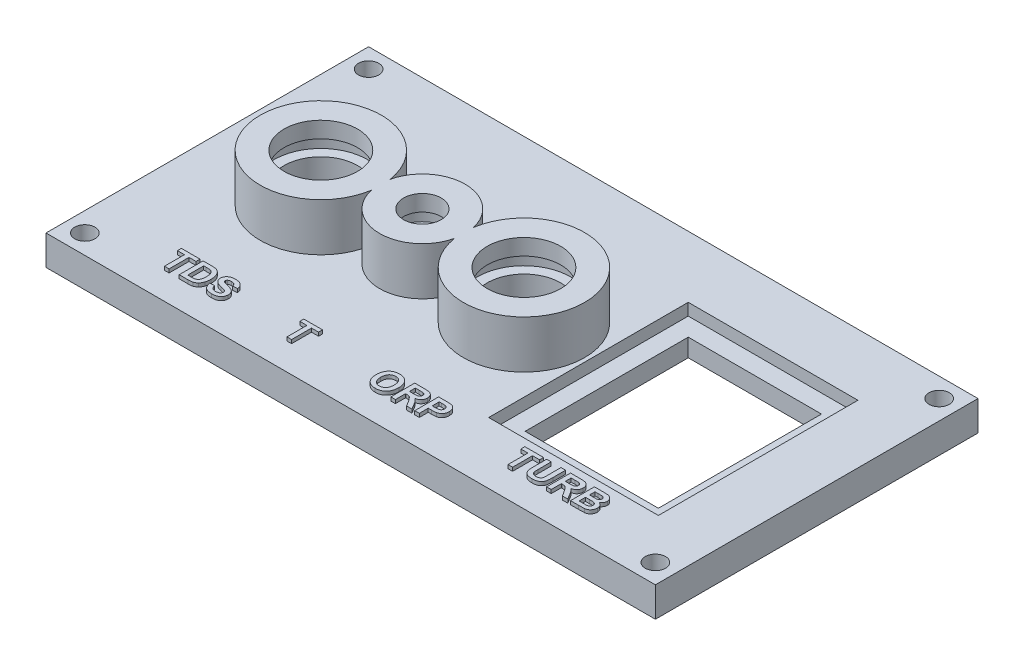
SolidWorks part; units mm, degrees
material "PETG"
ref_plane "Front Plane" through (0, 0, 0) normal (0, 0, 1) x (1, 0, 0)
ref_plane "Top Plane" through (0, 0, 0) normal (0, 1, 0) x (1, 0, 0)
ref_plane "Right Plane" through (0, 0, 0) normal (1, 0, 0) x (0, 0, -1)
other "Configuration Table"
sketch "Sketch1" plane through (0, 0, 0) normal (0, 1, 0) x (1, 0, 0)
  line L0 (-51, -27) -> (51, -27)
  line L1 (51, -27) -> (51, 27)
  line L2 (51, 27) -> (-51, 27)
  line L3 (-51, 27) -> (-51, -27)
extrude "Cap_Plate" add sketch "Sketch1" along normal blind 5
sketch "Sketch2" plane through (0, 0, 0) normal (0, 1, 0) x (1, 0, 0)
  circle A0 centre (-32, 0) radius 10.15
  dimension "D1" = 20.3
extrude "Collar_TDS" add sketch "Sketch2" along normal blind 8 from offset 5
sketch "Sketch3" plane through (0, 0, 0) normal (0, 1, 0) x (1, 0, 0)
  circle A0 centre (-15, 0) radius 7.15
  dimension "D1" = 14.3
extrude "Collar_T" add sketch "Sketch3" along normal blind 8 from offset 5
sketch "Sketch4" plane through (0, 0, 0) normal (0, 1, 0) x (1, 0, 0)
  circle A0 centre (2, 0) radius 10.15
  dimension "D1" = 20.3
extrude "Collar_ORP" add sketch "Sketch4" along normal blind 8 from offset 5
sketch "Sketch5" plane through (0, 0, 0) normal (0, 1, 0) x (1, 0, 0)
  circle A0 centre (-32, 0) radius 6.15
  dimension "D1" = 12.3
extrude "Port_TDS" cut sketch "Sketch5" along normal through all and the other way through all
sketch "Sketch6" plane through (0, 0, 0) normal (0, 1, 0) x (1, 0, 0)
  circle A0 centre (-32, 0) radius 7.85
  dimension "D1" = 15.7
extrude "ORing_Groove_TDS" cut sketch "Sketch6" along normal blind 2.6 from offset 7.7
sketch "Sketch7" plane through (0, 0, 0) normal (0, 1, 0) x (1, 0, 0)
  circle A0 centre (-15, 0) radius 3.15
  dimension "D1" = 6.3
extrude "Port_T" cut sketch "Sketch7" along normal through all and the other way through all
sketch "Sketch8" plane through (0, 0, 0) normal (0, 1, 0) x (1, 0, 0)
  circle A0 centre (-15, 0) radius 4.85
  dimension "D1" = 9.7
extrude "ORing_Groove_T" cut sketch "Sketch8" along normal blind 2.6 from offset 7.7
sketch "Sketch9" plane through (0, 0, 0) normal (0, 1, 0) x (1, 0, 0)
  circle A0 centre (2, 0) radius 6.15
  dimension "D1" = 12.3
extrude "Port_ORP" cut sketch "Sketch9" along normal through all and the other way through all
sketch "Sketch10" plane through (0, 0, 0) normal (0, 1, 0) x (1, 0, 0)
  circle A0 centre (2, 0) radius 7.85
  dimension "D1" = 15.7
extrude "ORing_Groove_ORP" cut sketch "Sketch10" along normal blind 2.6 from offset 7.7
sketch "Sketch11" plane through (0, 0, 0) normal (0, 1, 0) x (1, 0, 0)
  line L1 (15.85, -13.65) -> (38.15, -13.65)
  line L2 (15.85, -13.65) -> (15.85, 13.65)
  line L3 (15.85, 13.65) -> (38.15, 13.65)
  line L4 (38.15, -13.65) -> (38.15, 13.65)
  line L5 (15.85, -13.65) -> (38.15, 13.65) construction
  line L6 (15.85, 13.65) -> (38.15, -13.65) construction
  point P5 (27, 0)
  dimension "D1" = 22.3
  dimension "D2" = 27.3
extrude "Port_TURB" cut sketch "Sketch11" along normal through all and the other way through all
sketch "Sketch12" plane through (0, 0, 0) normal (0, 1, 0) x (1, 0, 0)
  line L1 (12.8, -16.7) -> (41.2, -16.7)
  line L2 (12.8, -16.7) -> (12.8, 16.7)
  line L3 (12.8, 16.7) -> (41.2, 16.7)
  line L4 (41.2, -16.7) -> (41.2, 16.7)
  line L5 (12.8, -16.7) -> (41.2, 16.7) construction
  line L6 (12.8, 16.7) -> (41.2, -16.7) construction
  point P5 (27, 0)
  dimension "D1" = 28.4
  dimension "D2" = 33.4
extrude "TURB_Gasket_Seat" cut sketch "Sketch12" against normal blind 2 from offset 5
sketch "Sketch13" plane through (0, 0, 0) normal (0, 1, 0) x (1, 0, 0)
  circle A0 centre (-47.75, 23.75) radius 1.7
  circle A1 centre (-47.75, -23.75) radius 1.7
  circle A2 centre (47.75, 23.75) radius 1.7
  circle A3 centre (47.75, -23.75) radius 1.7
  dimension "D1" = 3.4
  dimension "D2" = 3.4
  dimension "D3" = 3.4
  dimension "D4" = 3.4
extrude "Screw_Holes_M3" cut sketch "Sketch13" along normal through all and the other way through all
sketch "Sketch14" plane through (0, 0, 0) normal (0, 1, 0) x (1, 0, 0)
  text T0 "TDS" font "Arial" height 4
extrude "Label_TDS" add sketch "Sketch14" along normal blind 0.6 from offset 5
sketch "Sketch15" plane through (0, 0, 0) normal (0, 1, 0) x (1, 0, 0)
  text T0 "T" font "Arial" height 4
extrude "Label_T" add sketch "Sketch15" along normal blind 0.6 from offset 5
sketch "Sketch16" plane through (0, 0, 0) normal (0, 1, 0) x (1, 0, 0)
  text T0 "ORP" font "Arial" height 4
extrude "Label_ORP" add sketch "Sketch16" along normal blind 0.6 from offset 5
sketch "Sketch17" plane through (0, 0, 0) normal (0, 1, 0) x (1, 0, 0)
  text T0 "TURB" font "Arial" height 4
extrude "Label_TURB" add sketch "Sketch17" along normal blind 0.6 from offset 5
equation "\"Jar_OD\"= 90  'ASSUMED - Part C fallback - jar outer diameter"
equation "\"Jar_H\"= 120  'ASSUMED - Part C fallback - jar height"
equation "\"Pump_L\"= 45  'ASSUMED - Part C fallback"
equation "\"Pump_W\"= 24  'ASSUMED - Part C fallback"
equation "\"Pump_H\"= 33  'ASSUMED - Part C fallback"
equation "\"Pump_Outlet_OD\"= 7.5  'ASSUMED - Part C fallback"
equation "\"Tube_OD\"= 8  'ASSUMED - Part C fallback"
equation "\"Tube_ID\"= 6  'ASSUMED - Part C fallback"
equation "\"TDS_Body_Dia\"= 12  'ASSUMED - Part C fallback"
equation "\"TDS_Wet_Len\"= 45  'ASSUMED - Part C fallback - length in water"
equation "\"DS_Tube_Dia\"= 6  'ASSUMED - Part C fallback"
equation "\"DS_Tube_Len\"= 50  'ASSUMED - Part C fallback"
equation "\"ORP_Body_Dia\"= 12  'ASSUMED - Part C fallback"
equation "\"ORP_Body_Len\"= 150  'ASSUMED - Part C fallback"
equation "\"ORP_Cap_Dia\"= 16  'ASSUMED - Part C fallback"
equation "\"Turb_W\"= 33  'ASSUMED - Part C fallback - head width"
equation "\"Turb_D\"= 28  'ASSUMED - Part C fallback - head depth"
equation "\"Turb_H\"= 30  'ASSUMED - Part C fallback - head height"
equation "\"Turb_Slot_W\"= 10  'ASSUMED - Part C fallback - slot width"
equation "\"Flow_L\"= 62  'ASSUMED - Part C fallback YF-S201"
equation "\"Flow_W\"= 36  'ASSUMED - Part C fallback"
equation "\"Flow_H\"= 35  'ASSUMED - Part C fallback"
equation "\"Thread_G12_OD\"= 20.955  'ASSUMED - Part C fallback thread G1/2 (major diameter)"
equation "\"Valve_L\"= 75  'ASSUMED - Part C fallback"
equation "\"Valve_W\"= 45  'ASSUMED - Part C fallback"
equation "\"Valve_H\"= 60  'ASSUMED - Part C fallback"
equation "\"Tee_L\"= 40  'ASSUMED - Part C fallback - overall length"
equation "\"Tee_Branch_L\"= 25  'ASSUMED - Part C fallback"
equation "\"Tee_OD\"= 12  'ASSUMED - Part C fallback"
equation "\"Cuv_W\"= 12.5  'ASSUMED - Part C fallback"
equation "\"Cuv_D\"= 12.5  'ASSUMED - Part C fallback"
equation "\"Cuv_H\"= 45  'ASSUMED - Part C fallback"
equation "\"LED_Board_L\"= 20  'ASSUMED - Part C fallback"
equation "\"LED_Board_W\"= 20  'ASSUMED - Part C fallback - LED at centre"
equation "\"GUVA_L\"= 20  'ASSUMED - Part C fallback"
equation "\"GUVA_W\"= 12  'ASSUMED - Part C fallback - sensor at centre"
equation "\"Reed_L\"= 27  'ASSUMED - Part C fallback MC-38 half"
equation "\"Reed_W\"= 14  'ASSUMED - Part C fallback"
equation "\"Reed_H\"= 8  'ASSUMED - Part C fallback"
equation "\"ESP_L\"= 51  'ASSUMED - Part C fallback"
equation "\"ESP_W\"= 28  'ASSUMED - Part C fallback"
equation "\"TFT_L\"= 58  'ASSUMED - Part C fallback - board"
equation "\"TFT_W\"= 35  'ASSUMED - Part C fallback - board"
equation "\"TFT_Win_L\"= 35  'ASSUMED - Part C fallback - visible window"
equation "\"TFT_Win_W\"= 28  'ASSUMED - Part C fallback - visible window"
equation "\"Relay_L\"= 50  'ASSUMED - Part C fallback"
equation "\"Relay_W\"= 26  'ASSUMED - Part C fallback"
equation "\"Relay_H\"= 19  'ASSUMED - Part C fallback"
equation "\"Mosfet_L\"= 34  'ASSUMED - Part C fallback"
equation "\"Mosfet_W\"= 17  'ASSUMED - Part C fallback"
equation "\"Mosfet_H\"= 12  'ASSUMED - Part C fallback"
equation "\"TDS_Board_L\"= 42  'ASSUMED - Part C fallback"
equation "\"TDS_Board_W\"= 32  'ASSUMED - Part C fallback"
equation "\"Turb_Board_L\"= 38  'ASSUMED - Part C fallback"
equation "\"Turb_Board_W\"= 28  'ASSUMED - Part C fallback"
equation "\"BNC_Thread_Dia\"= 9.5  'ASSUMED - Part C fallback"
equation "\"Plate_L\"= 420  'ASSUMED - Part C fallback"
equation "\"Plate_W\"= 297  'ASSUMED - Part C fallback"
equation "\"Plate_T\"= 6  'ASSUMED - Part C fallback"
equation "\"Probe_Clr\"= 0.3  'DESIGN VALUE - Part C rule 3 - printed probe hole = diameter + 0.3"
equation "\"Cuv_Clr\"= 0.2  'DESIGN VALUE - Part C rule 3 - cuvette pocket = size + 0.2"
equation "\"Label_H\"= 0.6  'DESIGN VALUE - Part D - raised label height"
equation "\"D1@Sketch5\" = \"TDS_Body_Dia\" + \"Probe_Clr\""
equation "\"D1@Sketch6\" = \"TDS_Body_Dia\" + \"Probe_Clr\" + 2 * 1.7"
equation "\"D1@Sketch7\" = \"DS_Tube_Dia\" + \"Probe_Clr\""
equation "\"D1@Sketch8\" = \"DS_Tube_Dia\" + \"Probe_Clr\" + 2 * 1.7"
equation "\"D1@Sketch9\" = \"ORP_Body_Dia\" + \"Probe_Clr\""
equation "\"D1@Sketch10\" = \"ORP_Body_Dia\" + \"Probe_Clr\" + 2 * 1.7"
equation "\"D1@Sketch11\" = \"Turb_D\" - 2 * 3.0 + \"Probe_Clr\""
equation "\"D2@Sketch11\" = \"Turb_W\" - 2 * 3.0 + \"Probe_Clr\""
equation "\"D1@Sketch12\" = \"Turb_D\" + 0.4"
equation "\"D2@Sketch12\" = \"Turb_W\" + 0.4"
equation "\"D1@Label_TDS\" = \"Label_H\""
equation "\"D1@Label_T\" = \"Label_H\""
equation "\"D1@Label_ORP\" = \"Label_H\""
equation "\"D1@Label_TURB\" = \"Label_H\""
